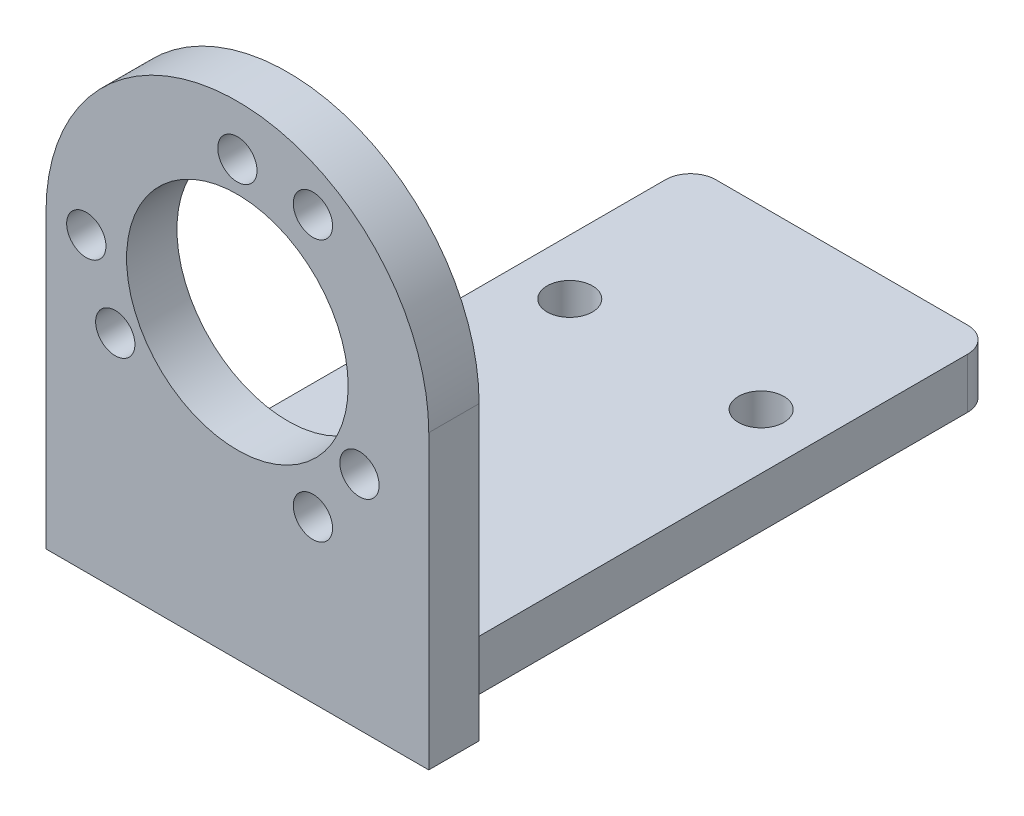
SolidWorks part; units mm, degrees
material "ABS"
ref_plane "Front Plane" through (0, 0, 0) normal (0, 0, 1) x (1, 0, 0)
ref_plane "Top Plane" through (0, 0, 0) normal (0, 1, 0) x (1, 0, 0)
ref_plane "Right Plane" through (0, 0, 0) normal (1, 0, 0) x (0, 0, -1)
sketch "Sketch1" plane through (0, 0, 0) normal (0, 0, 1) x (1, 0, 0)
  line L0 (-19, 0) -> (-19, -29)
  line L1 (-19, -29) -> (19, -29)
  line L2 (19, -29) -> (19, 0)
  circle A0 centre (0, 0) radius 19
  circle A1 centre (0, 0) radius 11
  dimension "D1" = 38
  dimension "D2" = 10
  dimension "D3" = 22
extrude "Boss-Extrude1" add sketch "Sketch1" along normal blind 5 contours A0 A1 | A0 L0 L1 L2
sketch "Sketch2" plane through (0, 0, 0) normal (0, 0, -1) x (-1, 0, 0)
  line L1 (-15, -29) -> (15, -29)
  line L2 (-15, -29) -> (-15, -24)
  line L3 (-15, -24) -> (15, -24)
  line L4 (15, -29) -> (15, -24)
  line L5 (19, -29) -> (-19, -29) construction
  point P8 (0, -24)
  dimension "D1" = 5
  dimension "D2" = 30
extrude "Boss-Extrude2" add sketch "Sketch2" along normal blind 55
hole_wizard "M3 Clearance Hole1" positions "Sketch3" profile "Sketch4" hole size "M3" standard "ANSI Metric" end condition up to next
sketch "Sketch3" plane through (0, 0, 5) normal (0, 0, 1) x (1, 0, 0)
  line L0 (0, 0) -> (0, 14) construction
  line L2 (0, 0) -> (7.5, 12.9904) construction
  circle A0 centre (0, 0) radius 14 construction
  circle A1 centre (0, 0) radius 15 construction
  point P5 (0, 14)
  point P14 (12.1244, -7)
  point P15 (-12.1244, -7)
  point P19 (7.5, 12.9904)
  point P32 (7.5, -12.9904)
  point P33 (-15, 0)
  dimension "D1" = 28
  dimension "D2" = 3
  dimension "D3" = 30
  dimension "D4" = 30
sketch "Sketch4" plane through (-15, 0, 5) normal (1, 0, 0) x (0, -1, 0)
  line L0 (0, 0) -> (0, 5)
  line L1 (0, 5) -> (1.95, 5)
  line L2 (1.95, 5) -> (1.95, 0)
  line L5 (1.95, 0) -> (0, 0)
  line L11 (0, -6.35) -> (0, 107.95) construction
  dimension "Thru Hole Dia." = 3.9
  dimension "Thru Hole Depth" = 5
hole_wizard "M4 Clearance Hole1" positions "Sketch5" profile "Sketch6" hole size "M4" standard "ANSI Metric" end condition up to next
sketch "Sketch5" plane through (0, -24, 0) normal (0, 1, 0) x (1, 0, 0)
  line L0 (9.5, 37.5) -> (-9.5, 37.5) construction
  line L1 (-15, 55) -> (15, 55) construction
  point P1 (-9.5, 37.5)
  point P20 (9.5, 37.5)
  point P24 (0, 37.5)
  dimension "D1" = 19
  dimension "D2" = 17.5
sketch "Sketch6" plane through (-9.5, -24, -37.5) normal (1, 0, 0) x (0, 0, 1)
  line L0 (0, 0) -> (0, 5)
  line L1 (0, 5) -> (2.25, 5)
  line L2 (2.25, 5) -> (2.25, 0)
  line L5 (2.25, 0) -> (0, 0)
  line L11 (0, -6.35) -> (0, 107.95) construction
  dimension "Thru Hole Dia." = 4.5
  dimension "Thru Hole Depth" = 5
fillet "Fillet1" radius 2.5 5 edges at (-15, -26.5, -55) (15, -26.5, -55) (0, -24, 0) (-15, -26.5, 0) (15, -26.5, 0)
